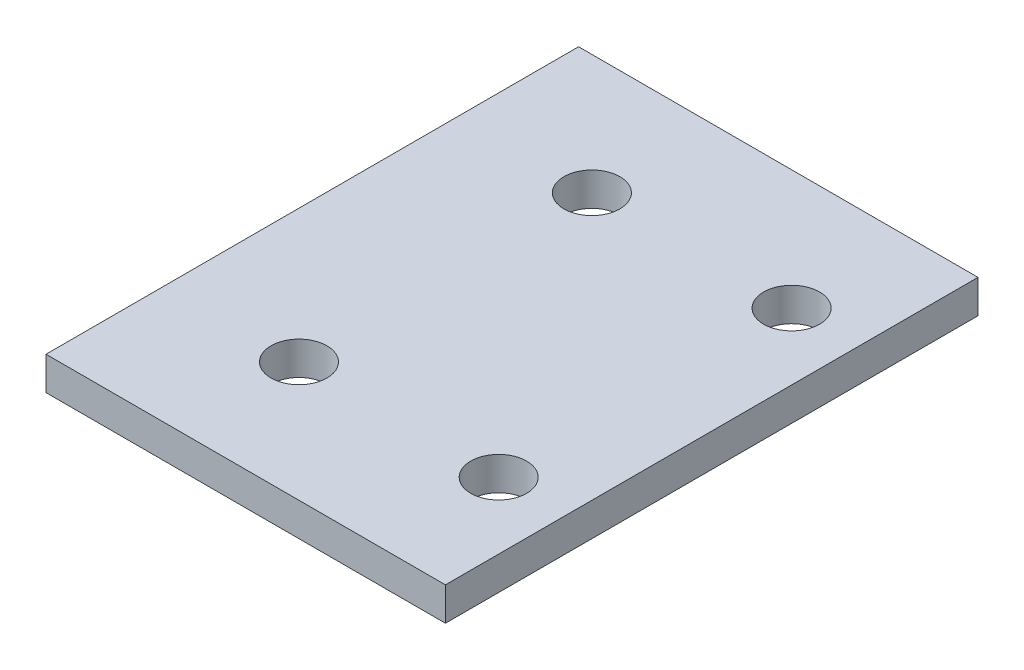
SolidWorks part; units mm, degrees
ref_plane "Front Plane" through (0, 0, 0) normal (0, 0, 1) x (1, 0, 0)
ref_plane "Top Plane" through (0, 0, 0) normal (0, 1, 0) x (1, 0, 0)
ref_plane "Right Plane" through (0, 0, 0) normal (1, 0, 0) x (0, 0, -1)
sketch "Sketch1" plane through (0, 0, 0) normal (0, 1, 0) x (1, 0, 0)
  line L0 (-15, 0) -> (15, 0) construction
  line L1 (-15, -20) -> (15, -20)
  line L2 (-15, -20) -> (-15, 20)
  line L3 (-15, 20) -> (15, 20)
  line L4 (15, -20) -> (15, 20)
  line L5 (-15, -20) -> (15, 20) construction
  line L6 (-15, 20) -> (15, -20) construction
  line L7 (2.5, 20) -> (2.5, -20) construction
  circle A0 centre (10, 11) radius 2.1
  circle A4 centre (-5, 11) radius 2.1
  circle A5 centre (10, -11) radius 2.1
  circle A6 centre (-5, -11) radius 2.1
  point P0 (0, 0)
  dimension "D3" = 4.2
  dimension "D1" = 40
  dimension "D2" = 30
  dimension "D4" = 11
  dimension "D5" = 5
  dimension "D6" = 7.5
extrude "Boss-Extrude1" add sketch "Sketch1" along normal blind 2.5
